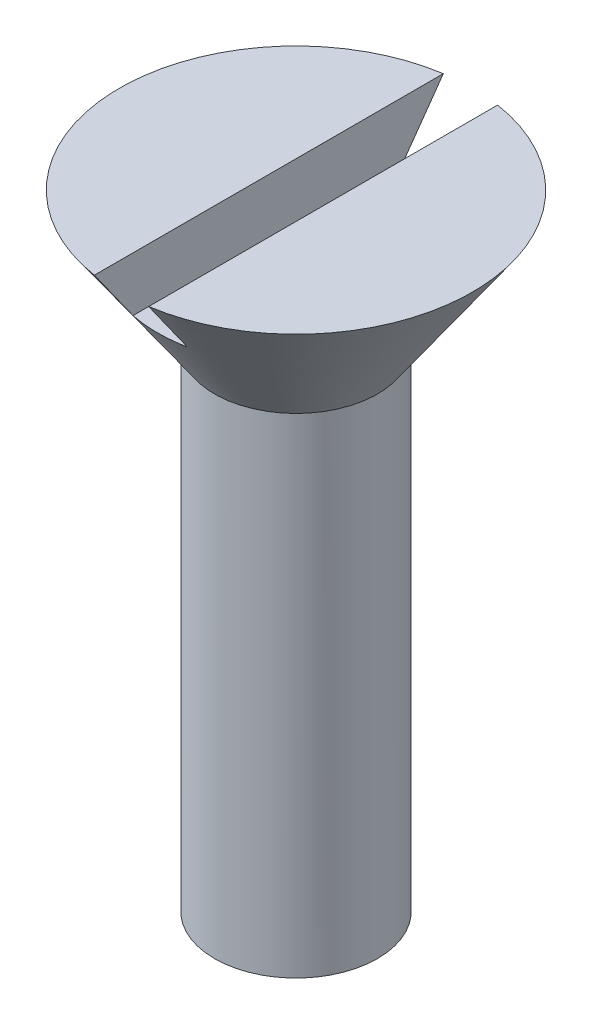
SolidWorks part; units mm, degrees
material "AISI Type A2 Tool Steel"
ref_plane "Front Plane" through (0, 0, 0) normal (0, 0, 1) x (1, 0, 0)
ref_plane "Top Plane" through (0, 0, 0) normal (0, 1, 0) x (1, 0, 0)
ref_plane "Right Plane" through (0, 0, 0) normal (1, 0, 0) x (0, 0, -1)
sketch "Sketch1" plane through (0, 0, 0) normal (0, 0, 1) x (1, 0, 0)
  line L0 (0, 0) -> (6.5, 0)
  line L1 (6.5, 0) -> (3, -5)
  line L2 (3, -5) -> (3, -23)
  line L3 (3, -23) -> (0, -24.7321)
  line L4 (0, -24.7321) -> (0, 0)
  dimension "D1" = 60
  dimension "D2" = 6.5
  dimension "D3" = 3
  dimension "D4" = 5
  dimension "D5" = 18
revolve "Revolve1" add sketch "Sketch1" angle 360 about L4
sketch "Sketch2" plane through (0, 0, 0) normal (0, 0, 1) x (1, 0, 0)
  line L1 (-1, 2) -> (1, 2)
  line L2 (-1, 2) -> (-1, -2)
  line L3 (-1, -2) -> (1, -2)
  line L4 (1, 2) -> (1, -2)
  line L5 (-1, 2) -> (1, -2) construction
  line L6 (-1, -2) -> (1, 2) construction
  point P0 (0, 0)
  dimension "D1" = 2
  dimension "D2" = 2
extrude "Cut-Extrude1" cut sketch "Sketch2" against normal mid plane 16
